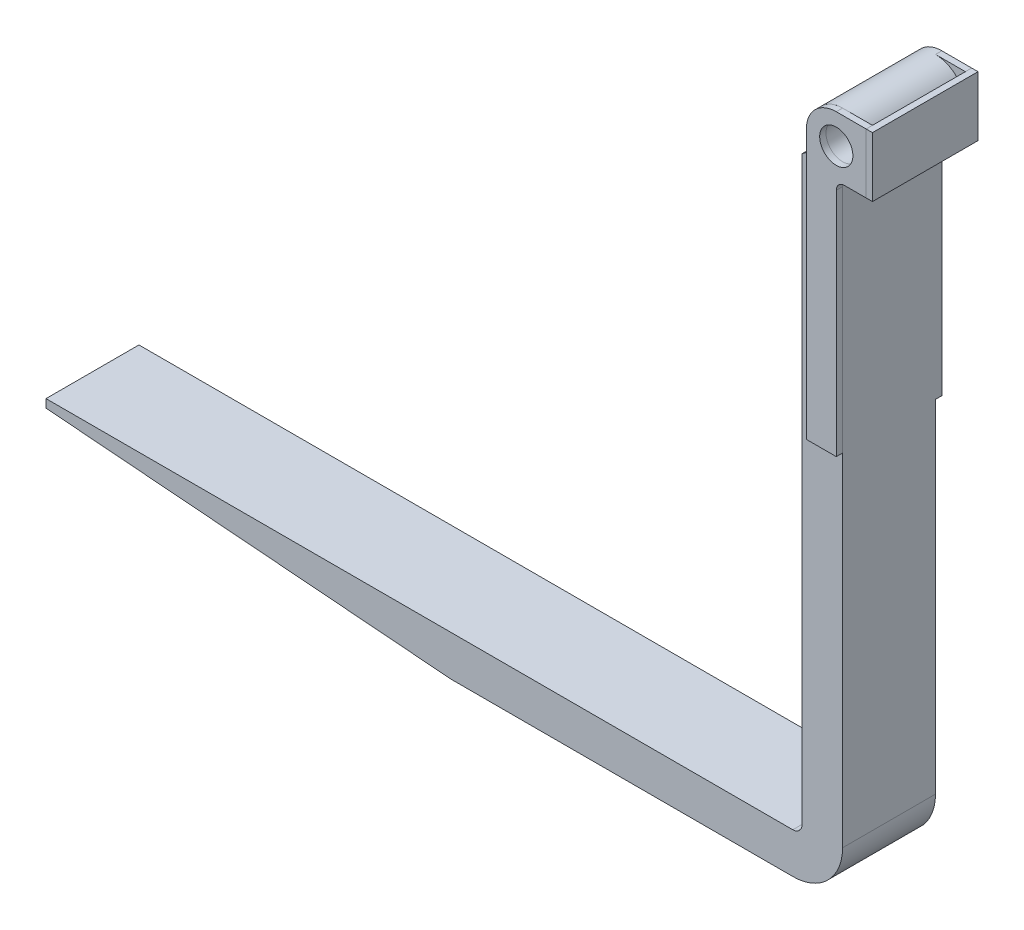
SolidWorks part; units mm, degrees
ref_plane "Front Plane" through (0, 0, 0) normal (0, 0, 1) x (1, 0, 0)
ref_plane "Top Plane" through (0, 0, 0) normal (0, 1, 0) x (1, 0, 0)
ref_plane "Right Plane" through (0, 0, 0) normal (1, 0, 0) x (0, 0, -1)
sketch "Sketch1" plane through (0, 0, 0) normal (0, 0, 1) x (1, 0, 0)
  line L0 (0, 950) -> (0, 75)
  line L1 (-75, 0) -> (-1200, 0)
  arc A0 (0, 75) -> (-75, 0) centre (-75, 75) cw
  point P6 (0, 0)
  dimension "D3" = 75
  dimension "D1" = 950
  dimension "D2" = 1200
extrude "Extrude-Thin1" add sketch "Sketch1" along normal mid plane 140 thin
sketch "Sketch2" plane through (0, 0, 70) normal (0, 0, 1) x (1, 0, 0)
  line L0 (-1200, 48.5) -> (-590, 0)
  line L1 (-1200, 0) -> (-1200, 61) construction
  line L2 (-75, 0) -> (-1200, 0) construction
  dimension "D1" = 12.5
  dimension "D2" = 610
extrude "Cut-Extrude1" cut sketch "Sketch2" against normal through all and the other way through all flip side to cut
sketch "Sketch3" plane through (0, 0, 0) normal (0, 0, 1) x (1, 0, 0)
  line L0 (0, 950) -> (0, 995) construction
  circle A0 centre (0, 995) radius 45
  circle A1 centre (0, 995) radius 25
  dimension "D1" = 50
  dimension "D2" = 90
extrude "Boss-Extrude1" add sketch "Sketch3" along normal mid plane 140 separate body
sketch "Sketch4" plane through (0, 0, 0) normal (0, 0, 1) x (1, 0, 0)
  line L0 (-61, 950) -> (0, 950) construction
  line L1 (-61, 950) -> (0, 950)
  line L2 (-61, 950) -> (-36.2126, 968.2858)
  circle A0 centre (0, 995) radius 45 construction
  circle A1 centre (0, 995) radius 45
extrude "Boss-Extrude2" add sketch "Sketch4" along normal mid plane 140 separate body contours A1 L2 L1
sketch "Sketch5" plane through (0, 0, 70) normal (0, 0, 1) x (1, 0, 0)
  line L0 (-45, 995) -> (-45, 590)
  line L1 (-45, 590) -> (0, 590)
  line L2 (0, 950) -> (0, 75) construction
  line L3 (0, 590) -> (0, 937.5)
  line L4 (12.5, 950) -> (45, 950)
  line L5 (45, 950) -> (45, 1040)
  line L6 (45, 1040) -> (0, 1040)
  circle A0 centre (0, 995) radius 45 construction
  arc A1 (0, 1040) -> (-45, 995) centre (0, 995) ccw
  arc A2 (0, 937.5) -> (12.5, 950) centre (12.5, 937.5) cw
  point P17 (0, 950)
  circle M1 centre (0, 995) radius 45
  circle M2 centre (0, 995) radius 25
  dimension "D1" = 12.5
  dimension "D2" = 450
  dimension "D3" = 45
extrude "Boss-Extrude3" add sketch "Sketch5" along normal blind 9.5 separate body contours L3 A2 L4 L5 L0 L1 M1 | M1 M2 | L5 L6 M1
mirror "Mirror1" about plane through (0, 0, 0) normal (0, 0, 1) of "Boss-Extrude3"
sketch "Sketch6" plane through (45, 0, 0) normal (1, 0, 0) x (0, 0, -1)
  line L1 (-79.5, 1040) -> (79.5, 1040)
  line L2 (-79.5, 1040) -> (-79.5, 950)
  line L3 (-79.5, 950) -> (79.5, 950)
  line L4 (79.5, 1040) -> (79.5, 950)
extrude "Boss-Extrude4" add sketch "Sketch6" along normal blind 9.5 separate body
